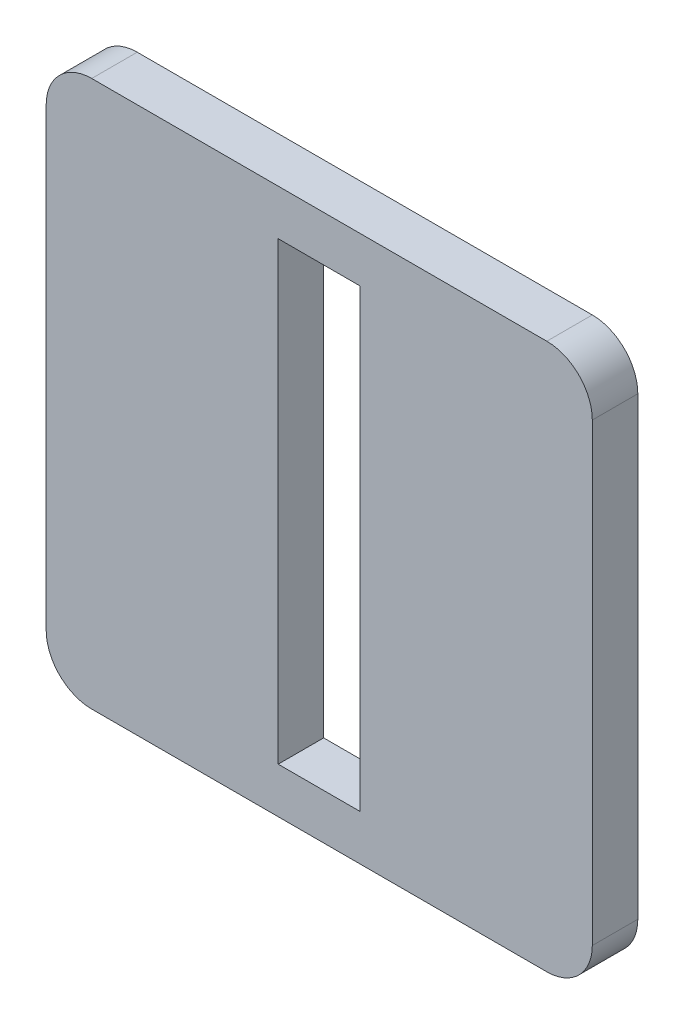
SolidWorks part; units mm, degrees
ref_plane "Front Plane" through (0, 0, 0) normal (0, 0, 1) x (1, 0, 0)
ref_plane "Top Plane" through (0, 0, 0) normal (0, 1, 0) x (1, 0, 0)
ref_plane "Right Plane" through (0, 0, 0) normal (1, 0, 0) x (0, 0, -1)
sketch "Sketch1" plane through (0, 0, 0) normal (0, 0, 1) x (1, 0, 0)
  line L1 (-50, 60) -> (50, 60)
  line L2 (-60, 50) -> (-60, -50)
  line L3 (-50, -60) -> (50, -60)
  line L4 (60, 50) -> (60, -50)
  line L5 (-60, 60) -> (60, -60) construction
  line L6 (-60, -60) -> (60, 60) construction
  arc A0 (-60, -50) -> (-50, -60) centre (-50, -50) ccw
  arc A1 (50, -60) -> (60, -50) centre (50, -50) ccw
  arc A2 (50, 60) -> (60, 50) centre (50, 50) cw
  arc A3 (-50, 60) -> (-60, 50) centre (-50, 50) ccw
  point P0 (0, 0)
  dimension "D3" = 10
  dimension "D1" = 120
  dimension "D2" = 120
extrude "Boss-Extrude1" add sketch "Sketch1" along normal blind 10 contours A3 L2 A0 L3 A1 L4 A2 L1
sketch "Sketch2" plane through (0, 0, 10) normal (0, 0, 1) x (1, 0, 0)
  line L0 (0, 0) -> (0, 40) construction
  line L1 (-50, 50) -> (50, 50) construction
  line L2 (-50, 50) -> (-50, -50) construction
  line L3 (-50, -50) -> (50, -50) construction
  line L4 (50, 50) -> (50, -50) construction
  line L5 (-50, 50) -> (50, -50) construction
  line L6 (-50, -50) -> (50, 50) construction
  line L7 (0, 40) -> (-40, 40) construction
  line L8 (-40, 40) -> (-40, 0) construction
  line L9 (-40, 0) -> (0, 0) construction
  line L11 (0, 20) -> (-20, 20) construction
  line L12 (-20, 40) -> (-20, 20) construction
  circle A0 centre (0, 40) radius 4 construction
  circle A1 centre (0, 20) radius 4 construction
  circle A2 centre (0, 0) radius 4 construction
  circle A3 centre (-20, 20) radius 4 construction
  circle A4 centre (-20, 40) radius 4 construction
  circle A5 centre (-40, 40) radius 4 construction
  circle A6 centre (0, 0) radius 4 construction
  circle A7 centre (20, 0) radius 4 construction
  circle A8 centre (40, 0) radius 4 construction
  circle A9 centre (40, 20) radius 4 construction
  circle A10 centre (40, 40) radius 4 construction
  circle A11 centre (20, 20) radius 4 construction
  circle A12 centre (0, 0) radius 4 construction
  circle A13 centre (0, -20) radius 4 construction
  circle A14 centre (0, -40) radius 4 construction
  circle A15 centre (20, -40) radius 4 construction
  circle A16 centre (40, -40) radius 4 construction
  circle A17 centre (20, -20) radius 4 construction
  circle A18 centre (0, 0) radius 4 construction
  circle A19 centre (-20, 0) radius 4 construction
  circle A20 centre (-40, 0) radius 4 construction
  circle A21 centre (-40, -20) radius 4 construction
  circle A22 centre (-40, -40) radius 4 construction
  circle A23 centre (-20, -20) radius 4 construction
  text T0 "I" font "Century Gothic" height 100
  point P0 (0, 0)
  point P55 (0, 0)
  dimension "D4" = 8
  dimension "D1" = 100
  dimension "D2" = 100
  dimension "D3" = 40
  dimension "D5" = 4
extrude "Cut-Extrude22" cut sketch "Sketch2" against normal blind 10
